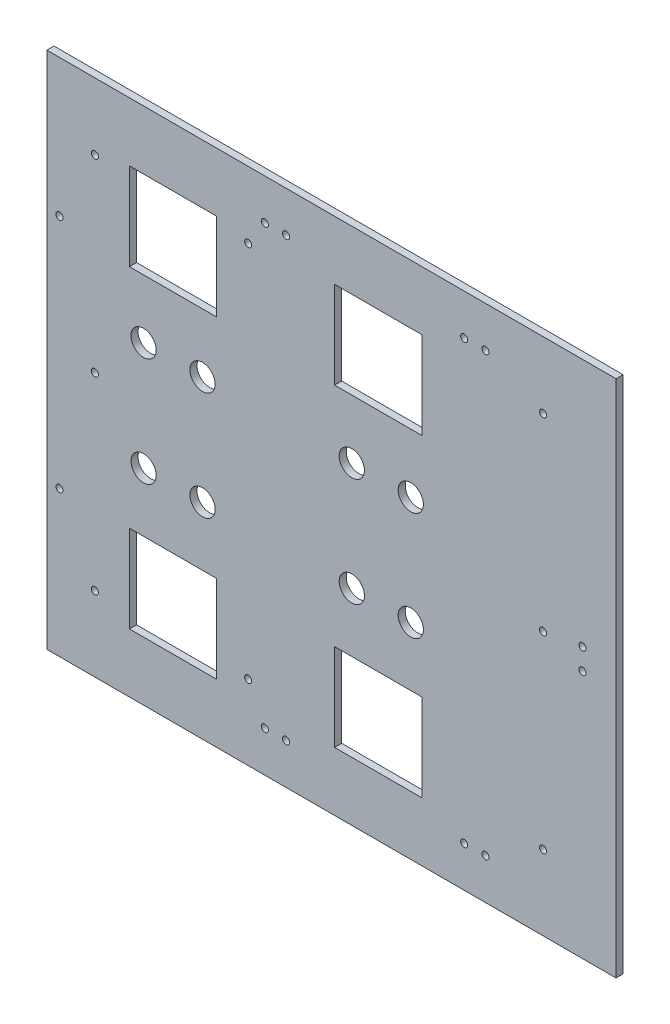
SolidWorks part; units mm, degrees
ref_plane "Front Plane" through (0, 0, 0) normal (0, 0, 1) x (1, 0, 0)
ref_plane "Top Plane" through (0, 0, 0) normal (0, 1, 0) x (1, 0, 0)
ref_plane "Right Plane" through (0, 0, 0) normal (1, 0, 0) x (0, 0, -1)
sketch "Sketch1" plane through (0, 0, 0) normal (0, 0, 1) x (1, 0, 0)
  line L1 (-64.7043, -84.8227) -> (176.5957, -84.8227)
  line L2 (-64.7043, -84.8227) -> (-64.7043, 125.1773)
  line L3 (-64.7043, 125.1773) -> (176.5957, 125.1773)
  line L4 (176.5957, -84.8227) -> (176.5957, 125.1773)
  dimension "D1" = 241.3
  dimension "D2" = 210
extrude "Boss-Extrude1" add sketch "Sketch1" along normal blind 3
sketch "Sketch2" plane through (0, 0, 3) normal (0, 0, 1) x (1, 0, 0)
  line L0 (-64.7043, 20.1773) -> (176.5957, 20.1773) construction
  line L1 (57.2957, 105.1773) -> (94.2957, 105.1773)
  line L2 (-29.7043, 68.1773) -> (7.2957, 68.1773)
  line L3 (-29.7043, 68.1773) -> (-29.7043, 105.1773)
  line L4 (-64.7043, 125.1773) -> (-64.7043, -84.8227)
  line L5 (-64.7043, -84.8227) -> (176.5957, -84.8227)
  line L6 (176.5957, -84.8227) -> (176.5957, 125.1773)
  line L7 (176.5957, 125.1773) -> (-64.7043, 125.1773)
  line L8 (-64.7043, 125.1773) -> (-64.7043, -84.8227)
  line L9 (-64.7043, -84.8227) -> (176.5957, -84.8227)
  line L10 (176.5957, -84.8227) -> (176.5957, 125.1773)
  line L11 (176.5957, 125.1773) -> (-64.7043, 125.1773)
  line L12 (-29.7043, 105.1773) -> (7.2957, 105.1773)
  line L13 (7.2957, 68.1773) -> (7.2957, 105.1773)
  line L14 (-29.7043, 68.1773) -> (7.2957, 105.1773) construction
  line L15 (-29.7043, 105.1773) -> (7.2957, 68.1773) construction
  line L16 (57.2957, 68.1773) -> (94.2957, 68.1773)
  line L17 (57.2957, 68.1773) -> (57.2957, 105.1773)
  line L18 (94.2957, 68.1773) -> (94.2957, 105.1773)
  line L19 (94.2957, -27.8227) -> (94.2957, -64.8227)
  line L20 (57.2957, -64.8227) -> (94.2957, -64.8227)
  line L21 (57.2957, -27.8227) -> (57.2957, -64.8227)
  line L22 (57.2957, -27.8227) -> (94.2957, -27.8227)
  line L23 (-29.7043, -64.8227) -> (7.2957, -64.8227)
  line L24 (7.2957, -27.8227) -> (7.2957, -64.8227)
  line L25 (-29.7043, -27.8227) -> (7.2957, -27.8227)
  line L26 (-29.7043, -27.8227) -> (-29.7043, -64.8227)
  point P6 (-11.2043, 86.6773)
  dimension "D2" = 37
  dimension "D3" = 37
  dimension "D4" = 20
  dimension "D5" = 20
  dimension "D6" = 50
  dimension "D7" = 35
  dimension "D1" = 0
extrude "Cut-Extrude1" cut sketch "Sketch2" against normal blind 3 contours L25 L26 L23 L24 | L22 L21 L20 L19 | L16 L18 L1 L17 | L2 L13 L12 L3
sketch "Sketch3" plane through (0, 0, 3) normal (0, 0, 1) x (1, 0, 0)
  line L0 (-64.7043, 20.1773) -> (256.7909, 20.1773) construction
  line L1 (-64.7043, 125.1773) -> (-64.7043, -84.8227) construction
  line L2 (-11.2043, 68.1773) -> (-11.2043, -27.8227) construction
  line L3 (-29.7043, 68.1773) -> (7.2957, 68.1773) construction
  line L4 (-29.7043, -27.8227) -> (7.2957, -27.8227) construction
  line L5 (-11.2043, -27.8227) -> (75.7957, 68.1773) construction
  line L6 (57.2957, 68.1773) -> (94.2957, 68.1773) construction
  line L7 (75.7957, 68.1773) -> (75.7957, -27.8227) construction
  line L8 (57.2957, -27.8227) -> (94.2957, -27.8227) construction
  line L9 (-11.2043, 43.1773) -> (77.0659, 43.1773)
  circle A2 centre (1.2957, 43.1773) radius 5.35
  circle A3 centre (-23.7043, 43.1773) radius 5.35
  circle A4 centre (64.5659, 43.1773) radius 5.35
  circle A5 centre (89.5659, 43.1773) radius 5.35
  circle A6 centre (89.5659, -2.8227) radius 5.35
  circle A7 centre (64.5659, -2.8227) radius 5.35
  circle A8 centre (1.2957, -2.8227) radius 5.35
  circle A9 centre (-23.7043, -2.8227) radius 5.35
  dimension "D1" = 25
  dimension "D2" = 25
extrude "Cut-Extrude2" cut sketch "Sketch3" against normal blind 3 contours A9 | A8 | A3 | A2 | A4 | A5 | A6 | A7
sketch "Sketch6" plane through (0, 0, 3) normal (0, 0, 1) x (1, 0, 0)
  line L0 (-44.3524, 21.9139) -> (266.0404, 21.9139) construction
  line L1 (-44.3524, -58.0861) -> (145.6476, -58.0861)
  line L2 (-44.3524, -58.0861) -> (-44.3524, 101.9139)
  line L3 (-44.3524, 101.9139) -> (145.6476, 101.9139)
  line L4 (145.6476, -58.0861) -> (145.6476, 101.9139)
  line L5 (-44.3524, -58.0861) -> (145.6476, 101.9139) construction
  line L6 (-44.3524, 101.9139) -> (145.6476, -58.0861) construction
  line L7 (-44.3524, -58.0861) -> (145.6476, 101.9139) construction
  line L8 (-44.3524, 101.9139) -> (145.6476, -58.0861) construction
  line L9 (-44.3524, -58.0861) -> (145.6476, -58.0861)
  line L10 (-44.3524, 101.9139) -> (145.6476, 101.9139)
  line L11 (-64.7043, 21.9139) -> (205.5347, 21.9139) construction
  line L15 (-64.7043, 125.1773) -> (-64.7043, -84.8227)
  line L16 (-64.7043, -84.8227) -> (176.5957, -84.8227)
  line L17 (176.5957, -84.8227) -> (176.5957, 125.1773)
  line L18 (176.5957, 125.1773) -> (-64.7043, 125.1773)
  line L19 (-64.7043, 125.1773) -> (-64.7043, -84.8227)
  line L20 (-64.7043, -84.8227) -> (176.5957, -84.8227)
  line L21 (176.5957, -84.8227) -> (176.5957, 125.1773)
  line L22 (176.5957, 125.1773) -> (-64.7043, 125.1773)
  circle A0 centre (-44.3524, 101.9139) radius 1.5
  circle A1 centre (145.6476, 101.9139) radius 1.5
  circle A2 centre (20.6476, 101.9139) radius 1.5
  circle A3 centre (80.6476, 101.9139) radius 1.5
  circle A4 centre (-44.3524, 21.9139) radius 1.5
  circle A5 centre (145.6476, 21.9139) radius 1.5
  circle A6 centre (80.6476, -58.0861) radius 1.5
  circle A7 centre (20.6476, -58.0861) radius 1.5
  circle A8 centre (145.6476, -58.0861) radius 1.5
  circle A9 centre (-44.3524, -58.0861) radius 1.5
  point P0 (50.6476, 21.9139)
  dimension "D5" = 3
  dimension "D6" = 3
  dimension "D7" = 0
  dimension "D1" = 190
  dimension "D2" = 160
  dimension "D3" = 65
  dimension "D4" = 65
extrude "Cut-Extrude3" cut sketch "Sketch6" against normal blind 3 contours L3 A0 L2 | L2 A0 L3 | L10 A2 | L10 A2 | L4 A1 L10 | L10 A1 L4 | L4 A5 | L4 A5 | A8 L4 L9 | A8 L9 L4 | A7 L9 | A7 L9 | A9 L2 L1 | A9 L1 L2 | L2 A4 | L2 A4
sketch "Sketch9" plane through (0, 125.1773, 0) normal (0, 1, 0) x (1, 0, 0)
  line L4 (176.5957, 0) -> (-64.7043, 0)
  line L5 (-64.7043, 0) -> (-64.7043, -3)
  line L6 (-64.7043, -3) -> (176.5957, -3)
  line L7 (176.5957, -3) -> (176.5957, 0)
  line L8 (176.5957, 0) -> (-64.7043, 0)
  line L9 (-64.7043, 0) -> (-64.7043, -3)
  line L10 (-64.7043, -3) -> (176.5957, -3)
  line L11 (176.5957, -3) -> (176.5957, 0)
  dimension "D1" = 0
extrude "Boss-Extrude2" add sketch "Sketch9" along normal blind 5
sketch "Sketch10" plane through (0, -84.8227, 0) normal (0, -1, 0) x (1, 0, 0)
  line L4 (-64.7043, 0) -> (176.5957, 0)
  line L5 (176.5957, 0) -> (176.5957, 3)
  line L6 (176.5957, 3) -> (-64.7043, 3)
  line L7 (-64.7043, 3) -> (-64.7043, 0)
  line L8 (-64.7043, 0) -> (176.5957, 0)
  line L9 (176.5957, 0) -> (176.5957, 3)
  line L10 (176.5957, 3) -> (-64.7043, 3)
  line L11 (-64.7043, 3) -> (-64.7043, 0)
  dimension "D1" = 0
extrude "Boss-Extrude3" add sketch "Sketch10" along normal blind 5
sketch "Sketch11" plane through (0, 0, 3) normal (0, 0, 1) x (1, 0, 0)
  line L0 (-64.7043, 130.1773) -> (-64.7043, -89.8227)
  line L1 (-64.7043, -89.8227) -> (176.5957, -89.8227)
  line L2 (176.5957, -89.8227) -> (176.5957, 130.1773)
  line L3 (176.5957, 130.1773) -> (-64.7043, 130.1773)
  line L4 (-64.7043, 130.1773) -> (-64.7043, -89.8227)
  line L5 (-64.7043, -89.8227) -> (176.5957, -89.8227)
  line L6 (176.5957, -89.8227) -> (176.5957, 130.1773)
  line L7 (176.5957, 130.1773) -> (-64.7043, 130.1773)
  line L8 (-64.7043, 130.1773) -> (-64.7043, -89.8227)
  line L9 (-64.7043, -89.8227) -> (176.5957, -89.8227)
  line L10 (176.5957, -89.8227) -> (176.5957, 130.1773)
  line L11 (176.5957, 130.1773) -> (-64.7043, 130.1773)
  line L12 (176.5957, 20.1773) -> (348.6749, 20.1773) construction
  line L13 (176.5957, -89.8227) -> (-64.7043, -89.8227)
  line L14 (-64.7043, 130.1773) -> (176.5957, 130.1773)
  line L15 (176.5957, -89.8227) -> (-64.7043, -89.8227)
  line L16 (-64.7043, 130.1773) -> (176.5957, 130.1773)
  circle A0 centre (121.2136, 112.9244) radius 1.5
  circle A1 centre (112.2136, 112.9244) radius 1.5
  circle A2 centre (36.7014, 112.9244) radius 1.5
  circle A3 centre (27.7014, 112.9244) radius 1.5
  circle A4 centre (-23.7043, -2.8227) radius 5.35
  circle A5 centre (1.2957, 43.1773) radius 5.35
  circle A6 centre (1.2957, -2.8227) radius 5.35
  circle A7 centre (-23.7043, 43.1773) radius 5.35
  circle A8 centre (27.7014, -72.5697) radius 1.5
  circle A9 centre (36.7014, -72.5697) radius 1.5
  circle A10 centre (112.2136, -72.5697) radius 1.5
  circle A11 centre (121.2136, -72.5697) radius 1.5
  dimension "D1" = 0
extrude "Cut-Extrude4" cut sketch "Sketch11" against normal blind 5 contours A3 | A2 | A1 | A0 | A11 | A10 | A9 | A8
sketch "Sketch12" plane through (0, 0, 3) normal (0, 0, 1) x (1, 0, 0)
  line L2 (176.5957, 130.1773) -> (176.5957, -89.8227)
  line L4 (-64.7043, 130.1773) -> (-64.7043, -89.8227)
  line L5 (-64.7043, -89.8227) -> (176.5957, -89.8227)
  line L6 (176.5957, -89.8227) -> (176.5957, 130.1773)
  line L7 (176.5957, 130.1773) -> (-64.7043, 130.1773)
  line L8 (-64.7043, 130.1773) -> (-64.7043, -89.8227)
  line L9 (-64.7043, -89.8227) -> (176.5957, -89.8227)
  line L10 (176.5957, -89.8227) -> (176.5957, 130.1773)
  line L11 (176.5957, 130.1773) -> (-64.7043, 130.1773)
  line L12 (176.5957, -89.8227) -> (-64.7043, -89.8227)
  line L13 (-64.7043, 130.1773) -> (176.5957, 130.1773)
  line L14 (-64.7043, -89.8227) -> (-64.7043, 130.1773)
  circle A4 centre (89.5659, 43.1773) radius 5.35
  circle A5 centre (89.5659, -2.8227) radius 5.35
  circle A6 centre (162.3419, 15.6773) radius 1.5
  circle A7 centre (162.3419, 24.6773) radius 1.5
  dimension "D1" = 0
extrude "Cut-Extrude5" cut sketch "Sketch12" against normal blind 10 contours A7 | A6
sketch "Sketch13" plane through (0, 0, 0) normal (0, 0, -1) x (-1, 0, 0)
  line L4 (64.7043, -89.8227) -> (64.7043, 130.1773)
  line L5 (64.7043, 130.1773) -> (-176.5957, 130.1773)
  line L6 (-176.5957, 130.1773) -> (-176.5957, -89.8227)
  line L7 (-176.5957, -89.8227) -> (64.7043, -89.8227)
  line L8 (64.7043, -89.8227) -> (64.7043, 130.1773)
  line L9 (64.7043, 130.1773) -> (-176.5957, 130.1773)
  line L10 (-176.5957, 130.1773) -> (-176.5957, -89.8227)
  line L11 (-176.5957, -89.8227) -> (64.7043, -89.8227)
  circle A0 centre (44.3524, 21.9139) radius 1.5 construction
  circle A1 centre (44.3524, 21.9139) radius 1.5
  circle A2 centre (59.3524, -28.0861) radius 1.5
  circle A3 centre (59.3524, 71.9139) radius 1.5
  dimension "D1" = 0
extrude "Cut-Extrude6" cut sketch "Sketch13" against normal blind 10 contours A3 | A2
